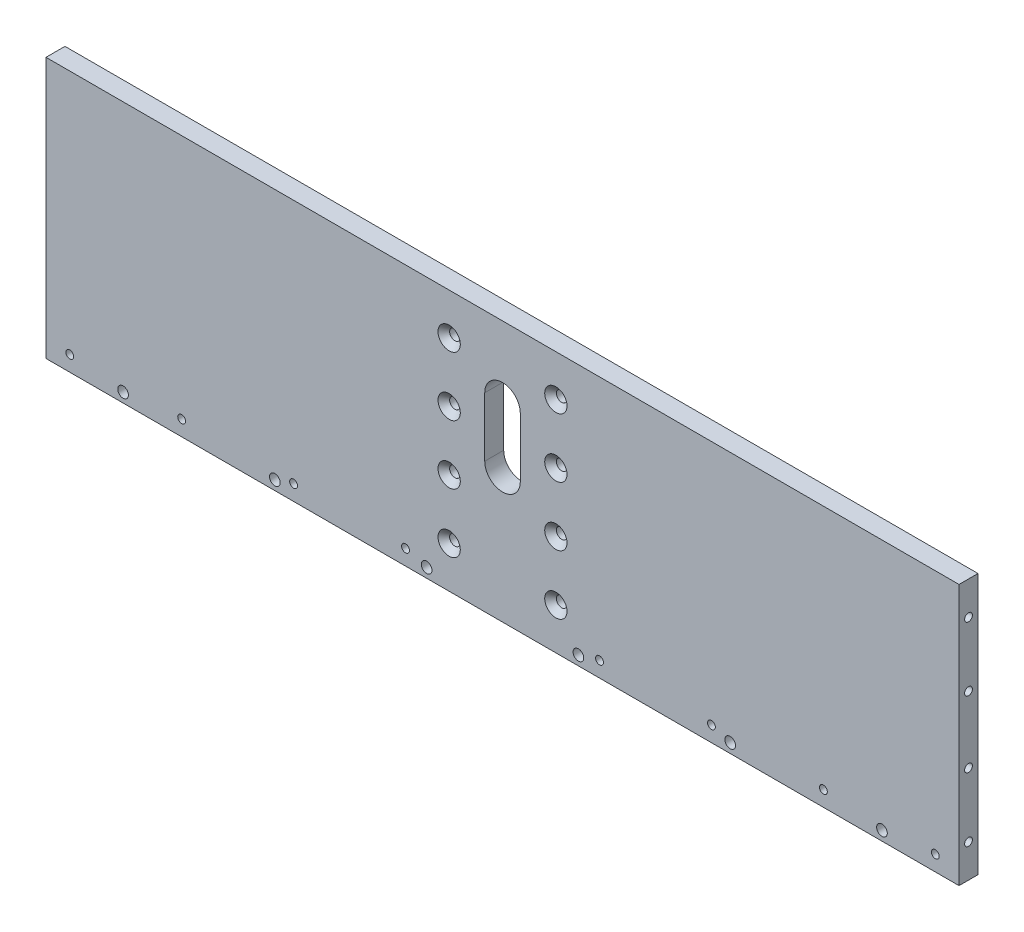
SolidWorks part; units mm, degrees
material "7079 Alloy"
ref_plane "Front Plane" through (0, 0, 0) normal (0, 0, 1) x (1, 0, 0)
ref_plane "Top Plane" through (0, 0, 0) normal (0, 1, 0) x (1, 0, 0)
ref_plane "Right Plane" through (0, 0, 0) normal (1, 0, 0) x (0, 0, -1)
sketch "Sketch1" plane through (0, 0, 0) normal (0, 0, 1) x (1, 0, 0)
  line L0 (-192.5, 0) -> (0, 0) construction
  line L1 (-192.5, -55) -> (192.5, -55)
  line L2 (-192.5, -55) -> (-192.5, 55)
  line L3 (-192.5, 55) -> (192.5, 55)
  line L4 (192.5, -55) -> (192.5, 55)
  line L5 (0, 0) -> (0, 55) construction
  dimension "D1" = 110
  dimension "D2" = 385
extrude "Extrude1" add sketch "Sketch1" along normal blind 8
sketch "Sketch2" plane through (0, 0, 8) normal (0, 0, 1) x (1, 0, 0)
  line L0 (0, 0) -> (0, 55) construction
  line L1 (192.5, 55) -> (-192.5, 55) construction
  line L6 (192.5, -55) -> (192.5, 55) construction
  line L7 (0, 0) -> (192.5, 0) construction
  circle A0 centre (22.5, 37.5) radius 2
  circle A1 centre (22.5, 12.5) radius 2
  circle A2 centre (22.5, -12.5) radius 2
  circle A3 centre (-22.5, -12.5) radius 2
  circle A4 centre (-22.5, -37.5) radius 2
  circle A5 centre (22.5, -37.5) radius 2
  circle A6 centre (-22.5, 12.5) radius 2
  circle A7 centre (-22.5, 37.5) radius 2
  dimension "D6" = 4
  dimension "D1" = 45
  dimension "D2" = 12.5
  dimension "D5" = 25
extrude "Cut-Extrude1" cut sketch "Sketch2" against normal blind 10
hole_wizard "CSK for M4 Flat Head Machine Screw1" positions "Sketch4" profile "Sketch3" countersink size "M4" standard "Ansi Metric" end condition through all
sketch "Sketch4" plane through (0, 0, 8) normal (0, 0, 1) x (1, 0, 0)
  point P1 (22.5, 37.5)
  point P4 (22.5, 12.5)
  point P19 (-22.5, 12.5)
  point P25 (-22.5, 37.5)
  point P33 (-22.5, -12.5)
  point P36 (22.5, -12.5)
  point P39 (22.5, -37.5)
  point P42 (-22.5, -37.5)
sketch "Sketch3" plane through (22.5, 37.5, 8) normal (1, 0, 0) x (0, -1, 0)
  line L0 (0, 0) -> (0, 8)
  line L1 (0, 8) -> (2.25, 8)
  line L2 (2.25, 8) -> (2.25, 2.45)
  line L3 (2.25, 2.45) -> (4.7, 0)
  line L5 (4.7, 0) -> (0, 0)
  line L6 (-2.25, 2.45) -> (-4.7, 0) construction
  line L11 (0, -6.35) -> (0, 107.95) construction
  dimension "Thru Hole Dia." = 4.5
  dimension "Thru Hole Depth" = 8
  dimension "Near C'Sink Dia." = 9.4
  dimension "Near C'Sink Angle" = 90
sketch "Sketch5" plane through (192.5, 0, 0) normal (1, 0, 0) x (0, 0, -1)
  line L0 (-4, 55) -> (-4, -55) construction
  line L1 (-8, 55) -> (0, 55) construction
  line L2 (-8, -55) -> (0, -55) construction
  line L3 (0, 0) -> (-8, 0) construction
  line L4 (0, -55) -> (0, 55) construction
  line L5 (-8, -55) -> (-8, 55) construction
  circle A0 centre (-4, 41) radius 1.65
  circle A1 centre (-4, 14) radius 1.65
  circle A2 centre (-4, -41) radius 1.65
  circle A3 centre (-4, -14) radius 1.65
  dimension "D1" = 3.3
  dimension "D3" = 27
  dimension "D2" = 14
extrude "Cut-Extrude2" cut sketch "Sketch5" against normal blind 15
mirror "Mirror1" about plane through (0, 0, 0) normal (1, 0, 0) of "Cut-Extrude2"
sketch "Sketch6" plane through (0, 0, 0) normal (0, 0, -1) x (-1, 0, 0)
  line L2 (0, -51) -> (-192.5, -51) construction
  line L3 (192.5, -55) -> (-192.5, -55) construction
  line L4 (-192.5, -55) -> (-192.5, 55) construction
  circle A0 centre (-96, -51) radius 2.25
  circle A1 centre (-32, -51) radius 2.25
  circle A2 centre (32, -51) radius 2.25
  circle A3 centre (96, -51) radius 2.25
  circle A4 centre (-160, -51) radius 2.25
  circle A5 centre (160, -51) radius 2.25
  dimension "D4" = 32.5
  dimension "D5" = 6
  dimension "D6" = 4.5
  dimension "D2" = 4
  dimension "D1" = 64
extrude "Cut-Extrude3" cut sketch "Sketch6" against normal blind 10
sketch "Sketch9" plane through (0, 0, 0) normal (0, 0, -1) x (-1, 0, 0)
  line L0 (-167.5, 40) -> (-167.5, -40) construction
  line L1 (-162.5, 40) -> (-162.5, -40)
  line L2 (-172.5, 40) -> (-172.5, -40)
  line L3 (-192.5, 55) -> (192.5, 55) construction
  line L4 (-192.5, -55) -> (-192.5, 55) construction
  line L5 (-154.5, 40) -> (-154.5, -40) construction
  line L6 (-149.5, 40) -> (-149.5, -40)
  line L7 (-159.5, 40) -> (-159.5, -40)
  line L8 (-141.5, 40) -> (-141.5, -40) construction
  line L9 (-136.5, 40) -> (-136.5, -40)
  line L10 (-146.5, 40) -> (-146.5, -40)
  line L11 (-128.5, 40) -> (-128.5, -40) construction
  line L12 (-123.5, 40) -> (-123.5, -40)
  line L13 (-133.5, 40) -> (-133.5, -40)
  line L14 (-115.5, 40) -> (-115.5, -40) construction
  line L15 (-110.5, 40) -> (-110.5, -40)
  line L16 (-120.5, 40) -> (-120.5, -40)
  line L17 (-102.5, 40) -> (-102.5, -40) construction
  line L18 (-97.5, 40) -> (-97.5, -40)
  line L19 (-107.5, 40) -> (-107.5, -40)
  line L20 (-89.5, 40) -> (-89.5, -40) construction
  line L21 (-84.5, 40) -> (-84.5, -40)
  line L22 (-94.5, 40) -> (-94.5, -40)
  line L23 (-76.5, 40) -> (-76.5, -40) construction
  line L24 (-71.5, 40) -> (-71.5, -40)
  line L25 (-81.5, 40) -> (-81.5, -40)
  line L26 (-63.5, 40) -> (-63.5, -40) construction
  line L27 (-58.5, 40) -> (-58.5, -40)
  line L28 (-68.5, 40) -> (-68.5, -40)
  line L29 (-50.5, 40) -> (-50.5, -40) construction
  line L30 (-45.5, 40) -> (-45.5, -40)
  line L31 (-55.5, 40) -> (-55.5, -40)
  line L32 (-37.5, 40) -> (-37.5, -40) construction
  line L33 (-32.5, 40) -> (-32.5, -40)
  line L34 (-42.5, 40) -> (-42.5, -40)
  line L35 (0, 0) -> (0, 55) construction
  line L36 (167.5, 40) -> (167.5, -40) construction
  line L37 (162.5, 40) -> (162.5, -40)
  line L38 (172.5, 40) -> (172.5, -40)
  line L39 (154.5, 40) -> (154.5, -40) construction
  line L40 (149.5, 40) -> (149.5, -40)
  line L41 (159.5, 40) -> (159.5, -40)
  line L42 (141.5, 40) -> (141.5, -40) construction
  line L43 (136.5, 40) -> (136.5, -40)
  line L44 (146.5, 40) -> (146.5, -40)
  line L45 (128.5, 40) -> (128.5, -40) construction
  line L46 (123.5, 40) -> (123.5, -40)
  line L47 (133.5, 40) -> (133.5, -40)
  line L48 (115.5, 40) -> (115.5, -40) construction
  line L49 (110.5, 40) -> (110.5, -40)
  line L50 (120.5, 40) -> (120.5, -40)
  line L51 (102.5, 40) -> (102.5, -40) construction
  line L52 (97.5, 40) -> (97.5, -40)
  line L53 (107.5, 40) -> (107.5, -40)
  line L54 (89.5, 40) -> (89.5, -40) construction
  line L55 (84.5, 40) -> (84.5, -40)
  line L56 (94.5, 40) -> (94.5, -40)
  line L57 (76.5, 40) -> (76.5, -40) construction
  line L58 (71.5, 40) -> (71.5, -40)
  line L59 (81.5, 40) -> (81.5, -40)
  line L60 (63.5, 40) -> (63.5, -40) construction
  line L61 (58.5, 40) -> (58.5, -40)
  line L62 (68.5, 40) -> (68.5, -40)
  line L63 (50.5, 40) -> (50.5, -40) construction
  line L64 (45.5, 40) -> (45.5, -40)
  line L65 (55.5, 40) -> (55.5, -40)
  line L66 (37.5, 40) -> (37.5, -40) construction
  line L67 (32.5, 40) -> (32.5, -40)
  line L68 (42.5, 40) -> (42.5, -40)
  arc A0 (-162.5, 40) -> (-172.5, 40) centre (-167.5, 40) ccw
  arc A1 (-172.5, -40) -> (-162.5, -40) centre (-167.5, -40) ccw
  arc A2 (-149.5, 40) -> (-159.5, 40) centre (-154.5, 40) ccw
  arc A3 (-159.5, -40) -> (-149.5, -40) centre (-154.5, -40) ccw
  arc A4 (-136.5, 40) -> (-146.5, 40) centre (-141.5, 40) ccw
  arc A5 (-146.5, -40) -> (-136.5, -40) centre (-141.5, -40) ccw
  arc A6 (-123.5, 40) -> (-133.5, 40) centre (-128.5, 40) ccw
  arc A7 (-133.5, -40) -> (-123.5, -40) centre (-128.5, -40) ccw
  arc A8 (-110.5, 40) -> (-120.5, 40) centre (-115.5, 40) ccw
  arc A9 (-120.5, -40) -> (-110.5, -40) centre (-115.5, -40) ccw
  arc A10 (-97.5, 40) -> (-107.5, 40) centre (-102.5, 40) ccw
  arc A11 (-107.5, -40) -> (-97.5, -40) centre (-102.5, -40) ccw
  arc A12 (-84.5, 40) -> (-94.5, 40) centre (-89.5, 40) ccw
  arc A13 (-94.5, -40) -> (-84.5, -40) centre (-89.5, -40) ccw
  arc A14 (-71.5, 40) -> (-81.5, 40) centre (-76.5, 40) ccw
  arc A15 (-81.5, -40) -> (-71.5, -40) centre (-76.5, -40) ccw
  arc A16 (-58.5, 40) -> (-68.5, 40) centre (-63.5, 40) ccw
  arc A17 (-68.5, -40) -> (-58.5, -40) centre (-63.5, -40) ccw
  arc A18 (-45.5, 40) -> (-55.5, 40) centre (-50.5, 40) ccw
  arc A19 (-55.5, -40) -> (-45.5, -40) centre (-50.5, -40) ccw
  arc A20 (-32.5, 40) -> (-42.5, 40) centre (-37.5, 40) ccw
  arc A21 (-42.5, -40) -> (-32.5, -40) centre (-37.5, -40) ccw
  arc A22 (162.5, 40) -> (172.5, 40) centre (167.5, 40) cw
  arc A23 (172.5, -40) -> (162.5, -40) centre (167.5, -40) cw
  arc A24 (149.5, 40) -> (159.5, 40) centre (154.5, 40) cw
  arc A25 (159.5, -40) -> (149.5, -40) centre (154.5, -40) cw
  arc A26 (136.5, 40) -> (146.5, 40) centre (141.5, 40) cw
  arc A27 (146.5, -40) -> (136.5, -40) centre (141.5, -40) cw
  arc A28 (123.5, 40) -> (133.5, 40) centre (128.5, 40) cw
  arc A29 (133.5, -40) -> (123.5, -40) centre (128.5, -40) cw
  arc A30 (110.5, 40) -> (120.5, 40) centre (115.5, 40) cw
  arc A31 (120.5, -40) -> (110.5, -40) centre (115.5, -40) cw
  arc A32 (97.5, 40) -> (107.5, 40) centre (102.5, 40) cw
  arc A33 (107.5, -40) -> (97.5, -40) centre (102.5, -40) cw
  arc A34 (84.5, 40) -> (94.5, 40) centre (89.5, 40) cw
  arc A35 (94.5, -40) -> (84.5, -40) centre (89.5, -40) cw
  arc A36 (71.5, 40) -> (81.5, 40) centre (76.5, 40) cw
  arc A37 (81.5, -40) -> (71.5, -40) centre (76.5, -40) cw
  arc A38 (58.5, 40) -> (68.5, 40) centre (63.5, 40) cw
  arc A39 (68.5, -40) -> (58.5, -40) centre (63.5, -40) cw
  arc A40 (45.5, 40) -> (55.5, 40) centre (50.5, 40) cw
  arc A41 (55.5, -40) -> (45.5, -40) centre (50.5, -40) cw
  arc A42 (32.5, 40) -> (42.5, 40) centre (37.5, 40) cw
  arc A43 (42.5, -40) -> (32.5, -40) centre (37.5, -40) cw
  point P2 (-167.5, 0)
  point P14 (-154.5, 0)
  point P21 (-141.5, 0)
  point P28 (-128.5, 0)
  point P35 (-115.5, 0)
  point P42 (-102.5, 0)
  point P49 (-89.5, 0)
  point P56 (-76.5, 0)
  point P63 (-63.5, 0)
  point P70 (-50.5, 0)
  point P77 (-37.5, 0)
  point P86 (167.5, 0)
  point P93 (154.5, 0)
  point P100 (141.5, 0)
  point P107 (128.5, 0)
  point P114 (115.5, 0)
  point P121 (102.5, 0)
  point P128 (89.5, 0)
  point P135 (76.5, 0)
  point P142 (63.5, 0)
  point P149 (50.5, 0)
  point P156 (37.5, 0)
  dimension "D1" = 15
  dimension "D2" = 80
  dimension "D3" = 10
  dimension "D4" = 25
  dimension "D6" = 13
  dimension "D5" = 11
extrude "Cut-Extrude4" cut sketch "Sketch9" against normal blind 6
sketch "Sketch10" plane through (0, 0, 8) normal (0, 0, 1) x (1, 0, 0)
  line L0 (0, 0) -> (0, 25) construction
  line L1 (-7.5, 0) -> (-7.5, 25)
  line L2 (7.5, 0) -> (7.5, 25)
  arc A0 (-7.5, 0) -> (7.5, 0) centre (0, 0) ccw
  arc A1 (7.5, 25) -> (-7.5, 25) centre (0, 25) ccw
  point P3 (0, 12.5)
  dimension "D1" = 7.5
  dimension "D2" = 25
extrude "Cut-Extrude5" cut sketch "Sketch10" against normal blind 10
hole_wizard "CSK for M4 Flat Head Machine Screw2" positions "Sketch12" profile "Sketch11" countersink size "M4" standard "Ansi Metric" end condition through all
sketch "Sketch12" plane through (0, 0, 0) normal (0, 0, -1) x (-1, 0, 0)
  point P1 (-160, -51)
  point P4 (-96, -51)
  point P7 (-32, -51)
  point P10 (32, -51)
  point P13 (96, -51)
  point P16 (160, -51)
sketch "Sketch11" plane through (160, -51, 0) normal (1, 0, 0) x (0, 1, 0)
  line L0 (0, 0) -> (0, 8)
  line L1 (0, 8) -> (2.25, 8)
  line L2 (2.25, 8) -> (2.25, 2.45)
  line L3 (2.25, 2.45) -> (4.7, 0)
  line L5 (4.7, 0) -> (0, 0)
  line L6 (-2.25, 2.45) -> (-4.7, 0) construction
  line L11 (0, -6.35) -> (0, 107.95) construction
  dimension "Thru Hole Dia." = 4.5
  dimension "Thru Hole Depth" = 8
  dimension "Near C'Sink Dia." = 9.4
  dimension "Near C'Sink Angle" = 90
sketch "Sketch14" plane through (0, 0, 0) normal (0, 0, -1) x (-1, 0, 0)
  line L0 (-192.5, -48.5) -> (0, -48.5) construction
  line L1 (-192.5, -55) -> (-192.5, 55) construction
  line L2 (0, -48.5) -> (0, -55) construction
  line L3 (29.5322, -55) -> (-29.5322, -55) construction
  line L4 (-98.4678, -55) -> (-157.5322, -55) construction
  circle A1 centre (-182.5, -48.5) radius 1.65
  circle A2 centre (-135.3, -48.5) radius 1.65
  circle A3 centre (-88.1, -48.5) radius 1.65
  circle A4 centre (-40.9, -48.5) radius 1.65
  circle A5 centre (40.9, -48.5) radius 1.65
  circle A6 centre (88.1, -48.5) radius 1.65
  circle A7 centre (135.3, -48.5) radius 1.65
  circle A8 centre (182.5, -48.5) radius 1.65
  dimension "D4" = 3.3
  dimension "D1" = 10
  dimension "D2" = 47.2
  dimension "D5" = 6.5
  dimension "D3" = 4
extrude "Cut-Extrude6" cut sketch "Sketch14" against normal blind 10
